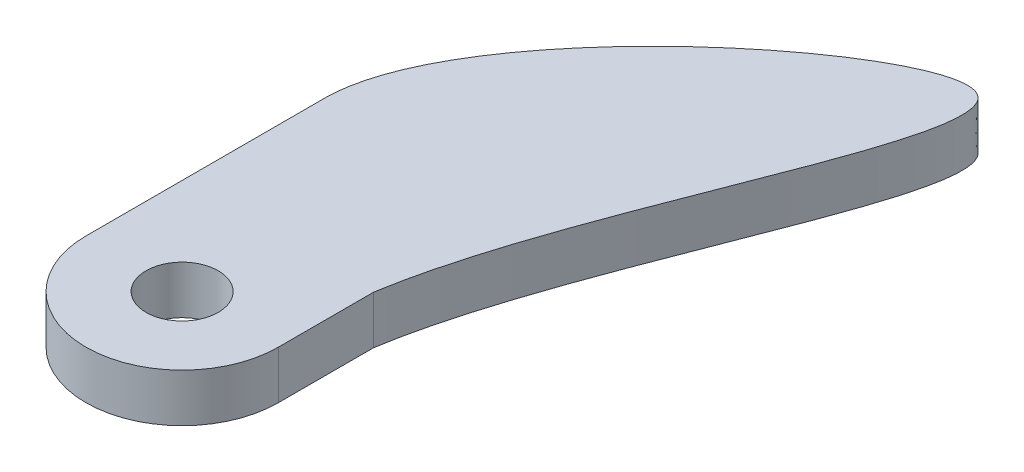
SolidWorks part; units mm, degrees
ref_plane "前视基准面" through (0, 0, 0) normal (0, 0, 1) x (1, 0, 0)
ref_plane "上视基准面" through (0, 0, 0) normal (0, 1, 0) x (1, 0, 0)
ref_plane "右视基准面" through (0, 0, 0) normal (1, 0, 0) x (0, 0, -1)
other "Configuration Table"
sketch "草图1" plane through (0, 0, 0) normal (0, 1, 0) x (1, 0, 0)
  line L0 (0, 0) -> (0, 20) construction
  line L1 (0, 20) -> (0, 0) construction
  line L2 (4, 3.9576) -> (4, 0)
  line L3 (-4, 10) -> (-4, 0)
  arc A1 (-4, 0) -> (4, 0) centre (0, 0) ccw
  circle A2 centre (0, 0) radius 1.5
  spline S0 degree 3 poles (4, 3.9576) (5.2203, 11.6179) (18.1051, 33.4825) (-3.8792, 15.9815) (-4, 10) knots 0.090091 0.090091 0.090091 0.090091 0.554983 1 1 1 1
  point P3 (0, 10)
  dimension "D2" = 3
  dimension "D1" = 20
  dimension "D3" = 8
extrude "凸台-拉伸1" add sketch "草图1" along normal blind 2
